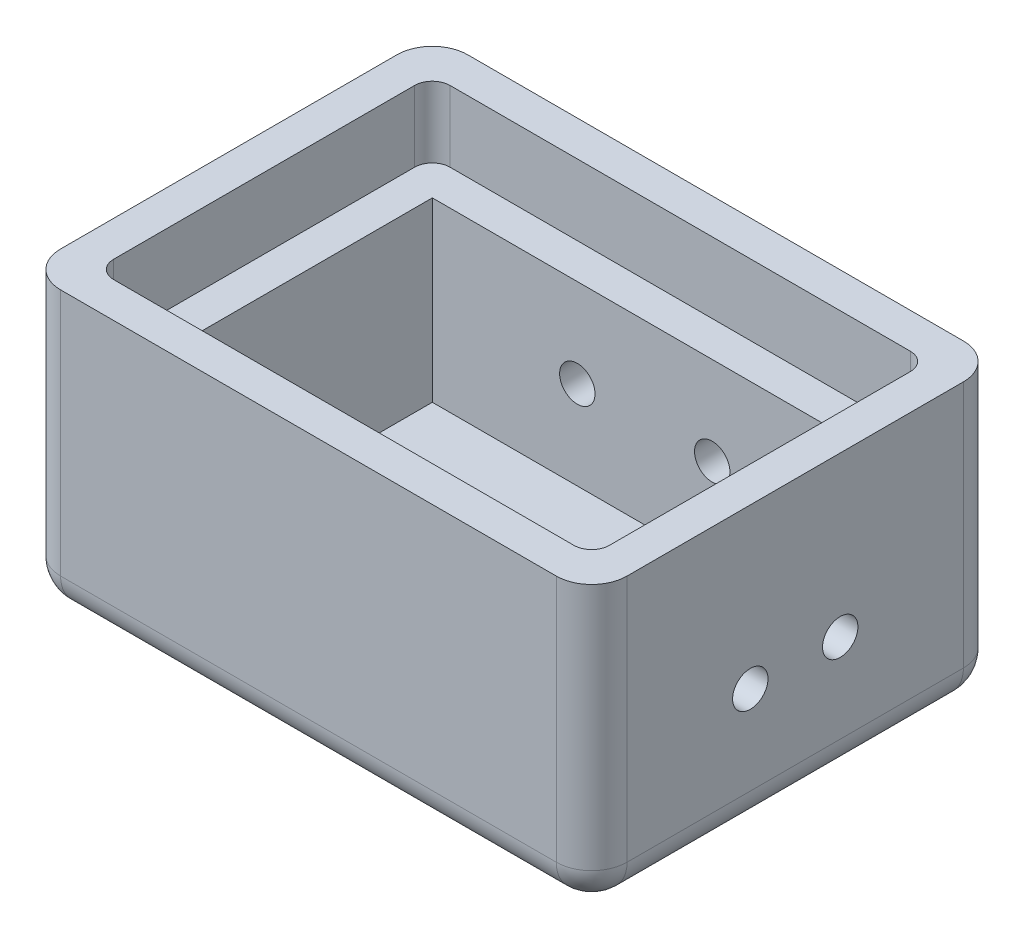
SolidWorks part; units mm, degrees
ref_plane "Alzado" through (0, 0, 0) normal (0, 0, 1) x (1, 0, 0)
ref_plane "Planta" through (0, 0, 0) normal (0, 1, 0) x (1, 0, 0)
ref_plane "Vista lateral" through (0, 0, 0) normal (1, 0, 0) x (0, 0, -1)
sketch "Croquis1" plane through (0, 0, 0) normal (0, 1, 0) x (1, 0, 0)
  line L1 (-6, -3.75) -> (6, -3.75) construction
  line L2 (-6, -3.75) -> (-6, 3.75) construction
  line L3 (-6, 3.75) -> (6, 3.75) construction
  line L4 (6, -3.75) -> (6, 3.75) construction
  line L5 (-6, -3.75) -> (6, 3.75) construction
  line L6 (-6, 3.75) -> (6, -3.75) construction
  line L7 (-7, -4.75) -> (7, -4.75) construction
  line L8 (-7, -4.75) -> (-7, 4.75) construction
  line L9 (-7, 4.75) -> (7, 4.75) construction
  line L10 (7, -4.75) -> (7, 4.75) construction
  line L11 (-7, -4.75) -> (7, 4.75) construction
  line L12 (-7, 4.75) -> (7, -4.75) construction
  line L13 (-8, -5.75) -> (8, -5.75)
  line L14 (-8, -5.75) -> (-8, 5.75)
  line L15 (-8, 5.75) -> (8, 5.75)
  line L16 (8, -5.75) -> (8, 5.75)
  line L17 (-8, -5.75) -> (8, 5.75) construction
  line L18 (-8, 5.75) -> (8, -5.75) construction
  point P0 (0, 0)
  point P6 (0, 0)
  point P11 (0, 0)
  dimension "D1" = 12
  dimension "D2" = 7.5
  dimension "D3" = 1
  dimension "D4" = 1
  dimension "D5" = 1
  dimension "D6" = 1
extrude "Saliente-Extruir2" add sketch "Croquis1" along normal blind 8 contours L15 L16 L13 L14
sketch "Croquis3" plane through (0, 8, 0) normal (0, 1, 0) x (1, 0, 0)
  line L0 (-8, -5.75) -> (-8, 5.75) construction
  line L1 (-7, -4.75) -> (7, -4.75)
  line L2 (-7, -4.75) -> (-7, 4.75)
  line L3 (-7, 4.75) -> (7, 4.75)
  line L4 (7, -4.75) -> (7, 4.75)
  line L5 (-7, -4.75) -> (7, 4.75) construction
  line L6 (-7, 4.75) -> (7, -4.75) construction
  line L7 (-8, 5.75) -> (8, 5.75) construction
  point P0 (0, 0)
  dimension "D1" = 1
  dimension "D2" = 1
extrude "Cortar-Extruir2" cut sketch "Croquis3" against normal blind 2
sketch "Croquis4" plane through (0, 6, 0) normal (0, 1, 0) x (1, 0, 0)
  line L0 (7, -4.75) -> (7, 4.75) construction
  line L1 (-6, -3.75) -> (6, -3.75)
  line L2 (-6, -3.75) -> (-6, 3.75)
  line L3 (-6, 3.75) -> (6, 3.75)
  line L4 (6, -3.75) -> (6, 3.75)
  line L5 (-6, -3.75) -> (6, 3.75) construction
  line L6 (-6, 3.75) -> (6, -3.75) construction
  line L7 (7, 4.75) -> (-7, 4.75) construction
  point P0 (0, 0)
  dimension "D1" = 1
  dimension "D2" = 1
extrude "Cortar-Extruir3" cut sketch "Croquis4" against normal offset from surface (5 mm away) 1 up to face at (0, 0, 0)
fillet "Redondeo1" radius 1 8 edges at (8, 4, -5.75) (8, 0, 0) (8, 4, 5.75) (0, 0, 5.75) (-8, 0, 0) (0, 0, -5.75) (-8, 4, -5.75) (-8, 4, 5.75)
fillet "Redondeo2" radius 0.5 4 edges at (7, 7, 4.75) (7, 7, -4.75) (-7, 7, -4.75) (-7, 7, 4.75)
sketch "Croquis5" plane through (6, 0, 0) normal (-1, 0, 0) x (0, 0, 1)
  line L0 (-1.27, 3.5) -> (1.27, 3.5) construction
  line L1 (3.75, 1) -> (-3.75, 1) construction
  line L2 (0, 3.5) -> (0, 1) construction
  line L3 (-3.75, 1) -> (-3.75, 6) construction
  line L4 (-3.75, 3.5) -> (-1.27, 3.5) construction
  circle A0 centre (-1.27, 3.5) radius 0.5
  circle A1 centre (1.27, 3.5) radius 0.5
  dimension "D2" = 1
  dimension "D1" = 2.54
extrude "Cortar-Extruir4" cut sketch "Croquis5" against normal up to next
sketch "Croquis6" plane through (0, 0, -3.75) normal (0, 0, 1) x (1, 0, 0)
  line L0 (-1.905, 3.5) -> (1.905, 3.5) construction
  line L1 (0, 3.5) -> (0, 1) construction
  line L2 (6, 1) -> (-6, 1) construction
  line L3 (-1.905, 3.5) -> (-6, 3.5) construction
  line L4 (-6, 1) -> (-6, 6) construction
  circle A0 centre (1.905, 3.5) radius 0.5
  circle A1 centre (-1.905, 3.5) radius 0.5
  dimension "D1" = 1
  dimension "D2" = 3.81
extrude "Cortar-Extruir5" cut sketch "Croquis6" against normal up to next
equation "\"D4@Croquis1\"=\"D3@Croquis1\""
equation "\"D6@Croquis1\"=\"D3@Croquis1\""
equation "\"D5@Croquis1\"=\"D3@Croquis1\""
equation "\"D1@Croquis3\"=\"D3@Croquis1\""
equation "\"D2@Croquis3\"=\"D3@Croquis1\""
equation "\"D1@Croquis4\"=\"D3@Croquis1\""
equation "\"D2@Croquis4\"=\"D3@Croquis1\""
equation "\"D1@Cortar-Extruir3\"=\"D3@Croquis1\""
